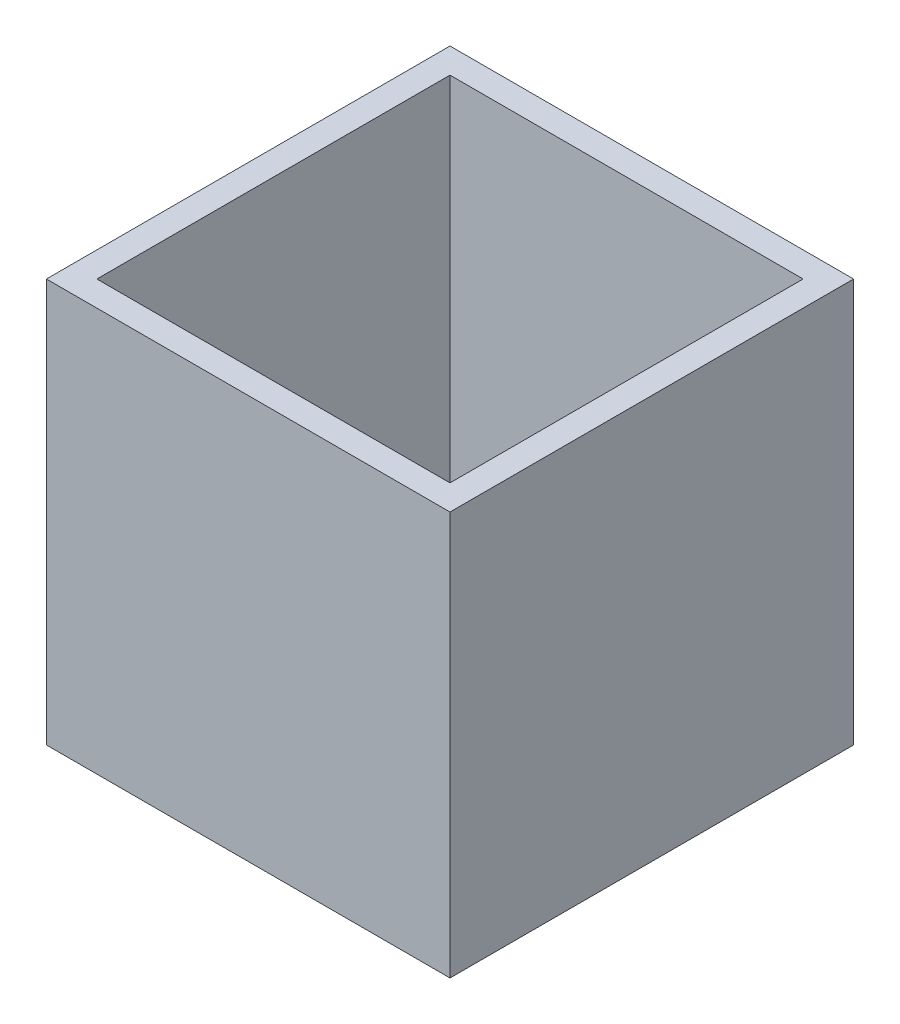
SolidWorks part; units mm, degrees
ref_plane "Front Plane" through (0, 0, 0) normal (0, 0, 1) x (1, 0, 0)
ref_plane "Top Plane" through (0, 0, 0) normal (0, 1, 0) x (1, 0, 0)
ref_plane "Right Plane" through (0, 0, 0) normal (1, 0, 0) x (0, 0, -1)
sketch "Sketch1" plane through (0, 0, 0) normal (0, 1, 0) x (1, 0, 0)
  line L0 (-11.1125, 11.1125) -> (11.1125, 11.1125)
  line L1 (-12.7, -12.7) -> (12.7, -12.7)
  line L2 (-12.7, -12.7) -> (-12.7, 12.7)
  line L3 (-12.7, 12.7) -> (12.7, 12.7)
  line L4 (12.7, -12.7) -> (12.7, 12.7)
  line L5 (-12.7, -12.7) -> (12.7, 12.7) construction
  line L6 (-12.7, 12.7) -> (12.7, -12.7) construction
  line L7 (11.1125, -11.1125) -> (11.1125, 11.1125)
  line L8 (-11.1125, -11.1125) -> (11.1125, -11.1125)
  line L9 (-11.1125, -11.1125) -> (-11.1125, 11.1125)
  point P0 (0, 0)
  dimension "D1" = 25.4
  dimension "D2" = 25.4
  dimension "D3" = 1.5875
extrude "Boss-Extrude1" add sketch "Sketch1" along normal blind 25.4
